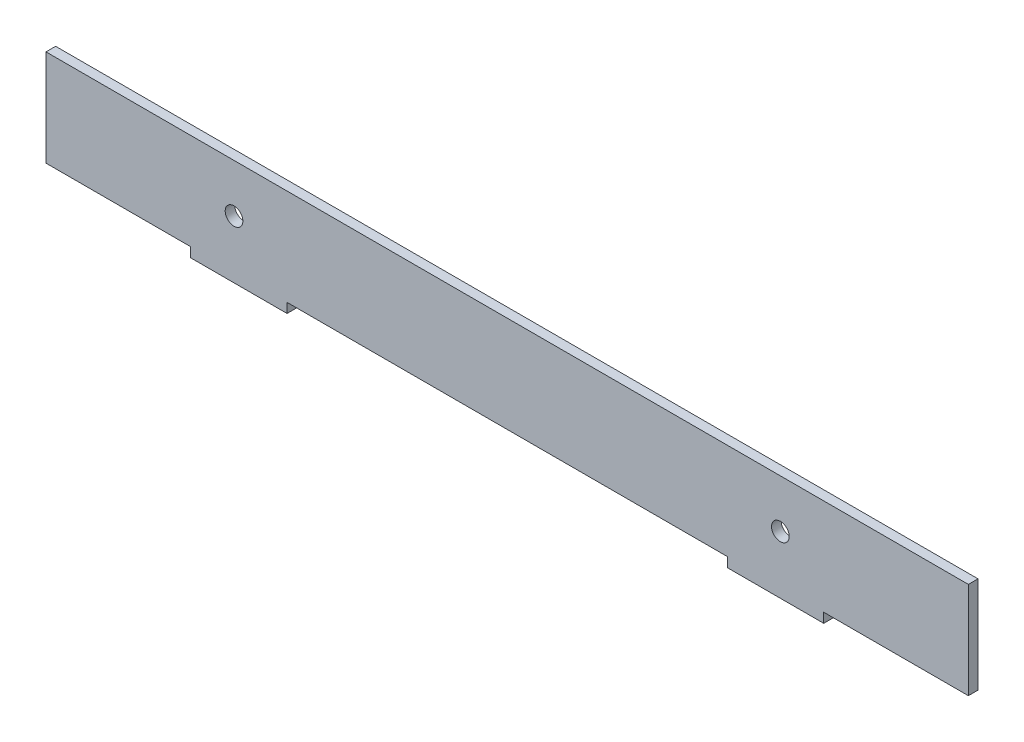
SolidWorks part; units mm, degrees
ref_plane "Alzado" through (0, 0, 0) normal (0, 0, 1) x (1, 0, 0)
ref_plane "Planta" through (0, 0, 0) normal (0, 1, 0) x (1, 0, 0)
ref_plane "Vista lateral" through (0, 0, 0) normal (1, 0, 0) x (0, 0, -1)
sketch "Croquis1" plane through (0, 0, 0) normal (0, 0, 1) x (1, 0, 0)
  line L0 (-20, 0) -> (20, 0) construction
  line L1 (-143.5, -15) -> (-98.5, -15)
  line L2 (-143.5, -15) -> (-143.5, 15)
  line L3 (-143.5, 15) -> (143.5, 15)
  line L4 (143.5, -15) -> (143.5, 15)
  line L5 (-143.5, -15) -> (143.5, 15) construction
  line L6 (-143.5, 15) -> (143.5, -15) construction
  line L7 (-20, 7.5) -> (20, 7.5) construction
  line L8 (-20, -7.5) -> (20, -7.5) construction
  line L9 (-68.5, -15) -> (68.5, -15)
  line L11 (-98.5, -15) -> (-98.5, -18)
  line L12 (-98.5, -18) -> (-68.5, -18)
  line L13 (-68.5, -15) -> (-68.5, -18)
  line L14 (0, 15) -> (0, -17.6964) construction
  line L15 (68.5, -15) -> (68.5, -18)
  line L16 (98.5, -18) -> (68.5, -18)
  line L17 (98.5, -15) -> (98.5, -18)
  line L18 (98.5, -15) -> (143.5, -15)
  arc A0 (-20, 7.5) -> (-20, -7.5) centre (-20, 0) ccw construction
  arc A1 (20, -7.5) -> (20, 7.5) centre (20, 0) ccw construction
  point P0 (0, 0)
  point P8 (0, 0)
  dimension "D3" = 7.5
  dimension "D1" = 287
  dimension "D2" = 30
  dimension "D4" = 7.5
  dimension "D5" = 40
  dimension "D6" = 3
  dimension "D7" = 45
  dimension "D8" = 30
extrude "Saliente-Extruir1" add sketch "Croquis1" along normal mid plane 3
hole_wizard "Taladro de margen para M51" positions "Croquis2" profile "Croquis3" hole size "M5" standard "ISO" end condition through all
sketch "Croquis2" plane through (0, 0, 1.5) normal (0, 0, 1) x (1, 0, 0)
  line L0 (143.5, 15) -> (-143.5, 15) construction
  point P0 (-85, 0)
  point P2 (85, 0)
  point P10 (0, 0)
  dimension "D1" = 170
  dimension "D2" = 85
  dimension "D3" = 15
sketch "Croquis3" plane through (-85, 0, 1.5) normal (1, 0, 0) x (0, -1, 0)
  line L0 (0, 0) -> (0, 3)
  line L1 (0, 3) -> (2.75, 3)
  line L2 (2.75, 3) -> (2.75, 0)
  line L5 (2.75, 0) -> (0, 0)
  line L11 (0, -6.35) -> (0, 107.95) construction
  dimension "Diámetro de taladro hasta el siguiente" = 5.5
  dimension "Profundidad de taladro hasta el siguiente" = 3
